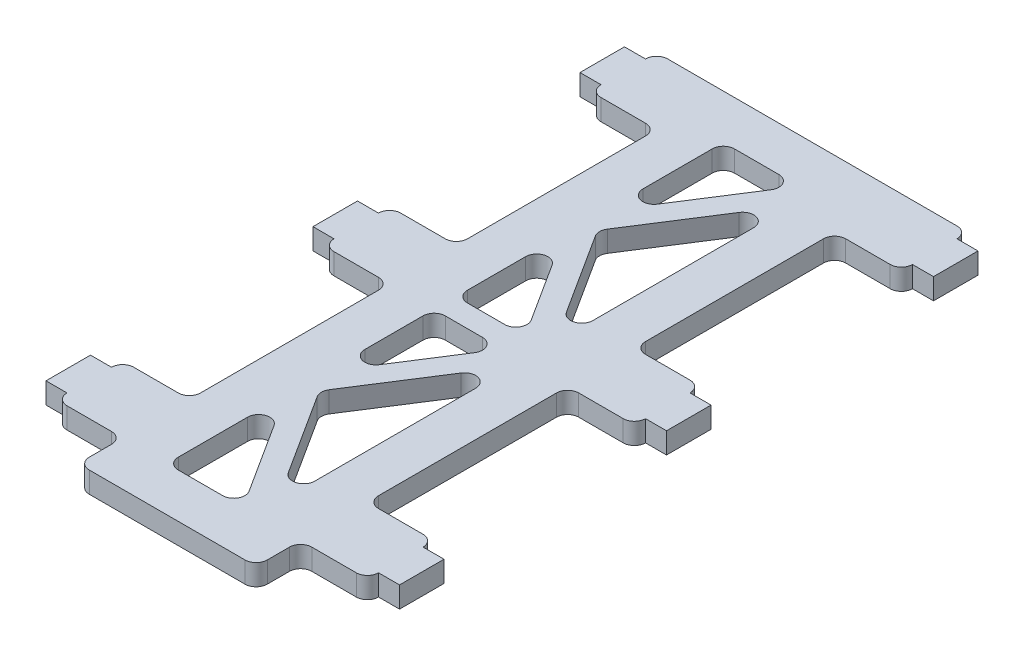
SolidWorks part; units mm, degrees
ref_plane "Front Plane" through (0, 0, 0) normal (0, 0, 1) x (1, 0, 0)
ref_plane "Top Plane" through (0, 0, 0) normal (0, 1, 0) x (1, 0, 0)
ref_plane "Right Plane" through (0, 0, 0) normal (1, 0, 0) x (0, 0, -1)
sketch "Sketch1" plane through (0, 34.29, 0) normal (0, 1, 0) x (1, 0, 0)
  line L0 (16.0528, 180.975) -> (19.05, 180.975) construction
  line L1 (0, -190.5) -> (0, 187.198) construction
  line L2 (38.1028, 187.198) -> (35.1028, 187.198) construction
  line L3 (35.1028, -190.5) -> (38.1, -190.5) construction
  line L5 (-12.7, 74.6125) -> (12.7, 74.6125)
  line L6 (-12.7, 74.6125) -> (-12.7, 166.6875)
  line L7 (-12.7, 166.6875) -> (12.7, 166.6875)
  line L8 (12.7, 74.6125) -> (12.7, 166.6875)
  line L9 (-12.7, 74.6125) -> (12.7, 166.6875) construction
  line L10 (-12.7, 166.6875) -> (12.7, 74.6125) construction
  point P0 (0, 120.65)
  dimension "D1" = 92.075
  dimension "D2" = 25.4
  dimension "D3" = 14.2875
extrude "Boss-Extrude1" add sketch "Sketch1" along normal mid plane 3 contours L7 L8 L5 L6
sketch "Sketch2" plane through (0, 35.79, 0) normal (0, 1, 0) x (1, 0, 0)
  line L0 (0, 166.6875) -> (0, 65.0186) construction
  line L1 (-12.7, 166.6875) -> (12.7, 166.6875) construction
  line L2 (12.7, 123.825) -> (-12.7, 123.825) construction
  line L5 (-22.225, 166.6875) -> (-12.7, 157.1625) construction
  line L6 (22.225, 157.1625) -> (12.7, 157.1625)
  line L7 (22.225, 157.1625) -> (22.225, 166.6875)
  line L8 (22.225, 166.6875) -> (12.7, 166.6875)
  line L9 (12.7, 157.1625) -> (12.7, 166.6875)
  line L10 (22.225, 157.1625) -> (12.7, 166.6875) construction
  line L11 (22.225, 166.6875) -> (12.7, 157.1625) construction
  line L12 (-22.225, 157.1625) -> (-12.7, 166.6875) construction
  line L13 (-12.7, 157.1625) -> (-12.7, 166.6875)
  line L14 (-22.225, 166.6875) -> (-12.7, 166.6875)
  line L15 (-22.225, 157.1625) -> (-22.225, 166.6875)
  line L16 (-22.225, 157.1625) -> (-12.7, 157.1625)
  line L17 (22.225, 119.0625) -> (12.7, 119.0625)
  line L18 (22.225, 119.0625) -> (22.225, 128.5875)
  line L19 (22.225, 128.5875) -> (12.7, 128.5875)
  line L20 (12.7, 119.0625) -> (12.7, 128.5875)
  line L21 (22.225, 119.0625) -> (12.7, 128.5875) construction
  line L22 (22.225, 128.5875) -> (12.7, 119.0625) construction
  line L23 (-12.7, 119.0625) -> (-12.7, 128.5875)
  line L24 (-22.225, 128.5875) -> (-12.7, 128.5875)
  line L25 (-22.225, 119.0625) -> (-22.225, 128.5875)
  line L26 (-22.225, 119.0625) -> (-12.7, 119.0625)
  line L27 (-22.225, 128.5875) -> (-12.7, 119.0625) construction
  line L28 (-22.225, 119.0625) -> (-12.7, 128.5875) construction
  line L29 (22.225, 80.9625) -> (12.7, 80.9625)
  line L30 (22.225, 80.9625) -> (22.225, 90.4875)
  line L31 (22.225, 90.4875) -> (12.7, 90.4875)
  line L32 (12.7, 80.9625) -> (12.7, 90.4875)
  line L33 (22.225, 80.9625) -> (12.7, 90.4875) construction
  line L34 (22.225, 90.4875) -> (12.7, 80.9625) construction
  line L35 (-12.7, 80.9625) -> (-12.7, 90.4875)
  line L36 (-22.225, 90.4875) -> (-12.7, 90.4875)
  line L37 (-22.225, 80.9625) -> (-22.225, 90.4875)
  line L38 (-22.225, 80.9625) -> (-12.7, 80.9625)
  line L39 (-22.225, 90.4875) -> (-12.7, 80.9625) construction
  line L40 (-22.225, 80.9625) -> (-12.7, 90.4875) construction
  point P7 (0, 0)
  point P11 (17.4625, 161.925)
  point P21 (-17.4625, 161.925)
  point P22 (0, 0)
  point P24 (17.4625, 123.825)
  point P33 (-17.4625, 123.825)
  point P34 (17.4625, 85.725)
  point P43 (-17.4625, 85.725)
  dimension "D1" = 9.525
  dimension "D2" = 9.525
  dimension "D4" = 38.1
  dimension "D3" = 3
extrude "Boss-Extrude2" add sketch "Sketch2" against normal up to surface (3 mm away) up to face at (0, 32.79, -120.65)
sketch "Sketch4" plane through (0, 35.79, 0) normal (0, 1, 0) x (1, 0, 0)
  line L0 (12.7, 128.5875) -> (12.7, 157.1625) construction
  line L1 (-6.35, 160.3375) -> (6.35, 160.3375)
  line L2 (-6.35, 160.3375) -> (-6.35, 80.9625)
  line L3 (-6.35, 80.9625) -> (6.35, 80.9625)
  line L4 (6.35, 160.3375) -> (6.35, 80.9625)
  line L5 (-6.35, 160.3375) -> (6.35, 80.9625) construction
  line L6 (-6.35, 80.9625) -> (6.35, 160.3375) construction
  line L7 (-12.7, 128.5875) -> (-12.7, 157.1625) construction
  line L8 (-22.225, 166.6875) -> (22.225, 166.6875) construction
  line L9 (-12.7, 74.6125) -> (12.7, 74.6125) construction
  line L10 (-6.35, 100.8063) -> (6.35, 100.8063) construction
  line L12 (-6.35, 100.8063) -> (6.35, 120.65) construction
  line L13 (6.35, 120.65) -> (-6.35, 140.4938) construction
  line L14 (6.35, 80.9625) -> (-6.35, 100.8063) construction
  line L15 (-6.35, 140.4938) -> (6.35, 140.4938) construction
  line L17 (7.6871, 81.8182) -> (-4.6614, 101.1128)
  line L18 (-6.35, 140.4938) -> (6.35, 160.3375) construction
  line L19 (6.35, 120.65) -> (-6.35, 120.65) construction
  line L20 (-7.6871, 101.662) -> (5.0129, 121.5057)
  line L21 (5.0129, 80.1068) -> (-8.0386, 100.4997)
  line L22 (6.35, 119.0625) -> (-6.35, 119.0625)
  line L23 (5.0129, 119.7943) -> (-8.2348, 140.4938)
  line L24 (-8.2348, 140.4938) -> (5.0129, 161.1932)
  line L25 (-4.6614, 101.1128) -> (7.9026, 160.0063) construction
  line L26 (-5.0129, 99.9505) -> (7.6871, 119.7943)
  line L27 (-6.35, 100.8063) -> (6.35, 160.3375) construction
  line L29 (6.35, 122.2375) -> (-6.35, 122.2375)
  line L30 (-8.0386, 100.4997) -> (4.7974, 160.6687) construction
  line L31 (7.6871, 121.5057) -> (-4.4652, 140.4938)
  line L32 (-4.4652, 140.4938) -> (7.6871, 159.4818)
  point P0 (0, 120.65)
  dimension "D1" = 6.35
  dimension "D2" = 6.35
  dimension "D3" = 6.35
  dimension "D4" = 6.35
  dimension "D7" = 1.5875
  dimension "D8" = 1.5875
  dimension "D9" = 1.5875
  dimension "D10" = 1.5875
extrude "Cut-Extrude1" cut sketch "Sketch4" against normal through all contours L3 L21 L2 | L26 L17 L4 | L20 L22 L2 | L29 L23 L2 | L32 L31 L4 | L2 L24 L1
fillet "Fillet1" radius 1.5875 42 edges at (-6.35, 34.29, -97.8613) (6.35, 34.29, -83.9075) (22.225, 34.29, -80.9625) (22.225, 34.29, -90.4875) (12.7, 34.29, -90.4875) (12.7, 34.29, -119.0625) (22.225, 34.29, -119.0625) (22.225, 34.29, -128.5875) (12.7, 34.29, -128.5875) (12.7, 34.29, -157.1625) (22.225, 34.29, -157.1625) (22.225, 34.29, -166.6875) (-22.225, 34.29, -157.1625) (-12.7, 34.29, -157.1625) (-12.7, 34.29, -128.5875) (-22.225, 34.29, -128.5875) (-22.225, 34.29, -119.0625) (-12.7, 34.29, -119.0625) (-12.7, 34.29, -90.4875) (-22.225, 34.29, -90.4875) (4.4652, 34.29, -80.9625) (-22.225, 34.29, -166.6875) (-6.35, 34.29, -137.5488) (3.4492, 34.29, -122.2375) (-6.35, 34.29, -122.2375) (6.35, 34.29, -117.705) (6.35, 34.29, -123.595) (-4.4652, 34.29, -140.4938) (6.35, 34.29, -157.3925) (-6.35, 34.29, -160.3375) (4.4652, 34.29, -160.3375) (-6.35, 34.29, -143.4387) (-6.35, 34.29, -103.7512) (-6.35, 34.29, -119.0625) (3.4492, 34.29, -119.0625) (-6.35, 34.29, -80.9625) (-4.4652, 34.29, -100.8063) (-12.7, 34.29, -74.6125) (12.7, 34.29, -74.6125) (12.7, 34.29, -80.9625) (-22.225, 34.29, -80.9625) (-12.7, 34.29, -80.9625)
sketch "Sketch5" plane through (0, 35.79, 0) normal (0, 1, 0) x (1, 0, 0)
  line L0 (22.225, 158.75) -> (22.225, 165.1) construction
  line L1 (25.225, 158.75) -> (22.225, 158.75)
  line L2 (25.225, 158.75) -> (25.225, 165.1)
  line L3 (25.225, 165.1) -> (22.225, 165.1)
  line L4 (22.225, 158.75) -> (22.225, 165.1)
  line L5 (25.225, 158.75) -> (22.225, 165.1) construction
  line L6 (25.225, 165.1) -> (22.225, 158.75) construction
  line L7 (22.225, 158.75) -> (22.225, 165.1) construction
  line L8 (22.225, 161.925) -> (23.725, 161.925) construction
  line L9 (0, 196.0278) -> (0, 0) construction
  line L10 (-22.225, 161.925) -> (-23.725, 161.925) construction
  line L11 (-25.225, 165.1) -> (-22.225, 158.75) construction
  line L12 (-25.225, 158.75) -> (-22.225, 165.1) construction
  line L13 (-22.225, 158.75) -> (-22.225, 165.1)
  line L14 (-25.225, 165.1) -> (-22.225, 165.1)
  line L15 (-25.225, 158.75) -> (-25.225, 165.1)
  line L16 (-25.225, 158.75) -> (-22.225, 158.75)
  line L17 (25.225, 120.65) -> (22.225, 120.65)
  line L18 (25.225, 120.65) -> (25.225, 127)
  line L19 (25.225, 127) -> (22.225, 127)
  line L20 (22.225, 120.65) -> (22.225, 127)
  line L21 (25.225, 120.65) -> (22.225, 127) construction
  line L22 (25.225, 127) -> (22.225, 120.65) construction
  line L23 (22.225, 123.825) -> (23.725, 123.825) construction
  line L24 (-22.225, 120.65) -> (-22.225, 127)
  line L25 (-25.225, 127) -> (-22.225, 127)
  line L26 (-25.225, 120.65) -> (-25.225, 127)
  line L27 (-25.225, 120.65) -> (-22.225, 120.65)
  line L28 (-22.225, 123.825) -> (-23.725, 123.825) construction
  line L29 (-25.225, 127) -> (-22.225, 120.65) construction
  line L30 (-25.225, 120.65) -> (-22.225, 127) construction
  line L31 (25.225, 82.55) -> (22.225, 82.55)
  line L32 (25.225, 82.55) -> (25.225, 88.9)
  line L33 (25.225, 88.9) -> (22.225, 88.9)
  line L34 (22.225, 82.55) -> (22.225, 88.9)
  line L35 (25.225, 82.55) -> (22.225, 88.9) construction
  line L36 (25.225, 88.9) -> (22.225, 82.55) construction
  line L37 (22.225, 85.725) -> (23.725, 85.725) construction
  line L38 (-22.225, 82.55) -> (-22.225, 88.9)
  line L39 (-25.225, 88.9) -> (-22.225, 88.9)
  line L40 (-25.225, 82.55) -> (-25.225, 88.9)
  line L41 (-25.225, 82.55) -> (-22.225, 82.55)
  line L42 (-22.225, 85.725) -> (-23.725, 85.725) construction
  line L43 (-25.225, 88.9) -> (-22.225, 82.55) construction
  line L44 (-25.225, 82.55) -> (-22.225, 88.9) construction
  line L45 (-23.725, 161.925) -> (-23.725, 123.825) construction
  point P0 (23.725, 161.925)
  point P7 (23.725, 123.825)
  point P21 (-23.725, 161.925)
  point P35 (-23.725, 123.825)
  point P36 (23.725, 85.725)
  point P49 (-23.725, 85.725)
  dimension "D1" = 3
  dimension "D2" = 6.35
  dimension "D4" = 38.1
  dimension "D3" = 3
extrude "Boss-Extrude3" add sketch "Sketch5" against normal up to surface (3 mm away)
